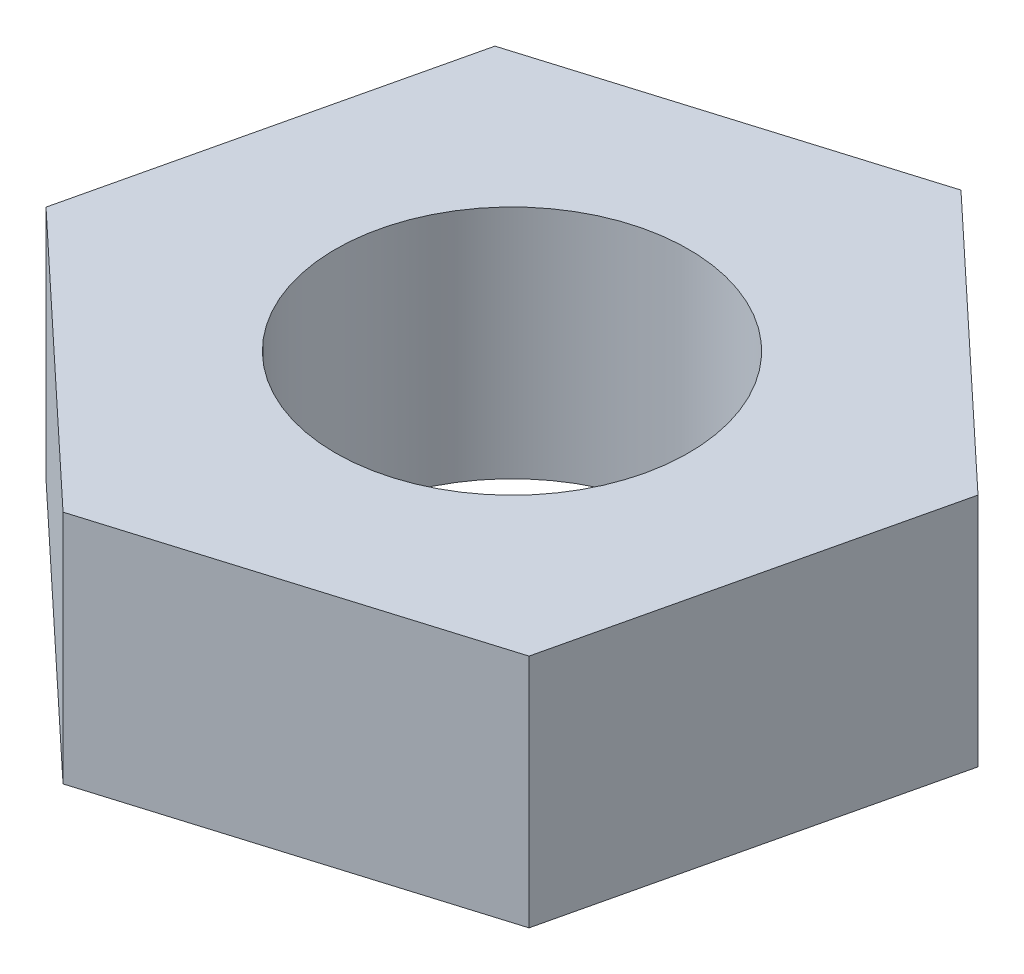
SolidWorks part; units mm, degrees
ref_plane "Front Plane" through (0, 0, 0) normal (0, 0, 1) x (1, 0, 0)
ref_plane "Top Plane" through (0, 0, 0) normal (0, 1, 0) x (1, 0, 0)
ref_plane "Right Plane" through (0, 0, 0) normal (1, 0, 0) x (0, 0, -1)
sketch "Sketch1" plane through (0, 0, 0) normal (0, 1, 0) x (1, 0, 0)
  line L1 (2.3166, -2.1718) -> (3.0391, 0.9203)
  line L2 (3.0391, 0.9203) -> (0.7225, 3.0921)
  line L3 (0.7225, 3.0921) -> (-2.3166, 2.1718)
  line L4 (-2.3166, 2.1718) -> (-3.0391, -0.9203)
  line L5 (-3.0391, -0.9203) -> (-0.7225, -3.0921)
  line L6 (-0.7225, -3.0921) -> (2.3166, -2.1718)
  circle A0 centre (0, 0) radius 2.75 construction
  circle A1 centre (0, 0) radius 1.5
extrude "Boss-Extrude1" add sketch "Sketch1" along normal blind 2
